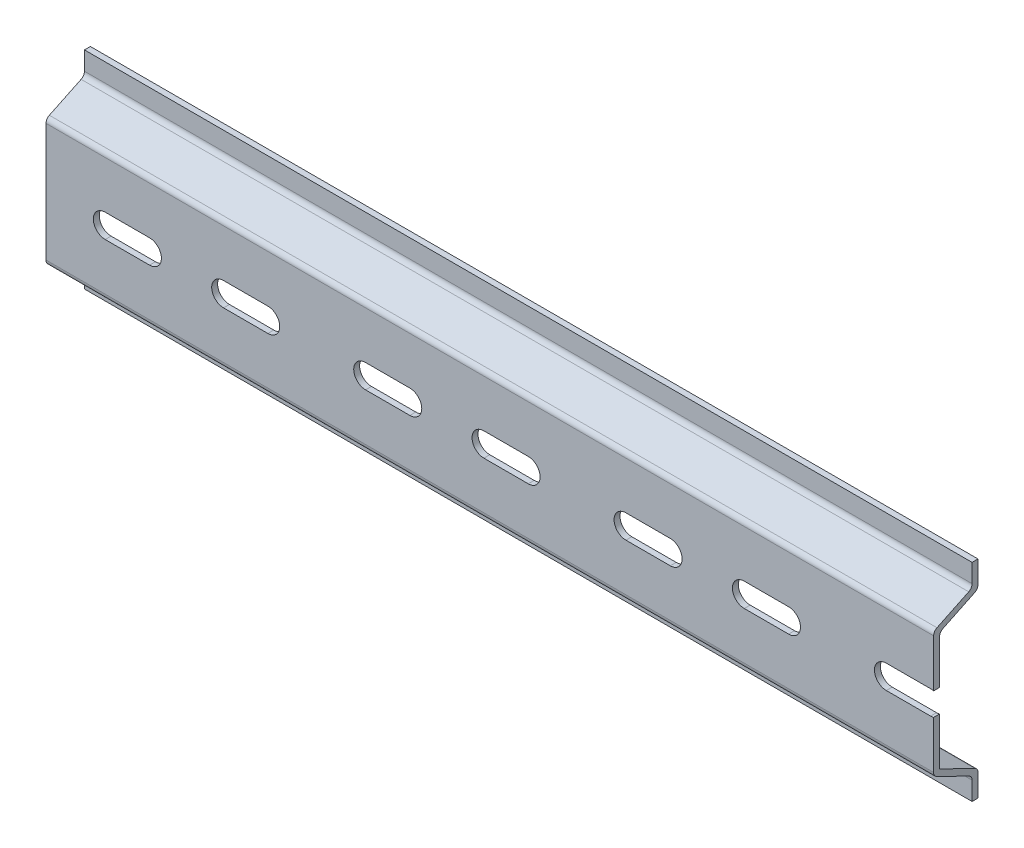
SolidWorks part; units mm, degrees
ref_plane "前视基准面" through (0, 0, 0) normal (0, 0, 1) x (1, 0, 0)
ref_plane "上视基准面" through (0, 0, 0) normal (0, 1, 0) x (1, 0, 0)
ref_plane "右视基准面" through (0, 0, 0) normal (1, 0, 0) x (0, 0, -1)
sketch "草图1" plane through (0, 0, 0) normal (1, 0, 0) x (0, 0, -1)
  line L0 (0, -10) -> (0, 10)
  line L1 (0, 10) -> (6.5, 13.1208)
  line L2 (6.5, 13.1208) -> (6.5, 17.5)
  line L3 (6.5, 17.5) -> (5.5, 17.5)
  line L4 (5.5, 17.5) -> (5.5, 13.75)
  line L5 (5.5, 13.75) -> (-1, 10.6292)
  line L6 (-1, 10.6292) -> (-1, -10.6292)
  line L7 (-14.3812, 0) -> (24.228, 0) construction
  line L8 (5.5, -13.75) -> (-1, -10.6292)
  line L9 (5.5, -17.5) -> (5.5, -13.75)
  line L10 (6.5, -17.5) -> (5.5, -17.5)
  line L11 (6.5, -13.1208) -> (6.5, -17.5)
  line L12 (0, -10) -> (6.5, -13.1208)
  point P12 (-1, 0)
  point P17 (0, 0)
  dimension "D1" = 7.5
  dimension "D2" = 1
  dimension "D3" = 1
  dimension "D4" = 1
  dimension "D5" = 27.5
  dimension "D6" = 35
  dimension "D7" = 20
extrude "凸台-拉伸1" add sketch "草图1" along normal blind 150
fillet "圆角1" radius 1 7 edges at (75, 13.75, -5.5) (75, 10.6292, 1) (75, 10, 0) (75, -10.6292, 1) (75, -13.1208, -6.5) (75, -13.75, -5.5) (75, 13.1208, -6.5)
sketch "草图2" plane through (0, 0, 0) normal (0, 0, -1) x (-1, 0, 0)
  line L0 (33.4315, 0) -> (-53.4315, 0) construction
  line L1 (-10, 0) -> (-17.5, 0) construction
  line L2 (-10, -2) -> (-17.5, -2)
  line L3 (-10, 2) -> (-17.5, 2)
  line L4 (-30, 0) -> (-37.5, 0) construction
  line L5 (-30, -2) -> (-37.5, -2)
  line L6 (-30, 2) -> (-37.5, 2)
  line L7 (-54, 0) -> (-61.5, 0) construction
  line L8 (-54, -2) -> (-61.5, -2)
  line L9 (-54, 2) -> (-61.5, 2)
  line L10 (-74, 0) -> (-81.5, 0) construction
  line L11 (-74, -2) -> (-81.5, -2)
  line L12 (-74, 2) -> (-81.5, 2)
  line L13 (-98, 0) -> (-105.5, 0) construction
  line L14 (-98, -2) -> (-105.5, -2)
  line L15 (-98, 2) -> (-105.5, 2)
  line L16 (-118, 0) -> (-125.5, 0) construction
  line L17 (-118, -2) -> (-125.5, -2)
  line L18 (-118, 2) -> (-125.5, 2)
  line L19 (-142, 0) -> (-149.5, 0) construction
  line L20 (-142, -2) -> (-149.5, -2)
  line L21 (-142, 2) -> (-149.5, 2)
  line L22 (-162, 0) -> (-169.5, 0) construction
  line L23 (-162, -2) -> (-169.5, -2)
  line L24 (-162, 2) -> (-169.5, 2)
  line L25 (-186, 0) -> (-193.5, 0) construction
  line L26 (-186, -2) -> (-193.5, -2)
  line L27 (-186, 2) -> (-193.5, 2)
  line L28 (-206, 0) -> (-213.5, 0) construction
  line L29 (-206, -2) -> (-213.5, -2)
  line L30 (-206, 2) -> (-213.5, 2)
  line L31 (-230, 0) -> (-237.5, 0) construction
  line L32 (-230, -2) -> (-237.5, -2)
  line L33 (-230, 2) -> (-237.5, 2)
  line L34 (-250, 0) -> (-257.5, 0) construction
  line L35 (-250, -2) -> (-257.5, -2)
  line L36 (-250, 2) -> (-257.5, 2)
  line L37 (-274, 0) -> (-281.5, 0) construction
  line L38 (-274, -2) -> (-281.5, -2)
  line L39 (-274, 2) -> (-281.5, 2)
  line L40 (-294, 0) -> (-301.5, 0) construction
  line L41 (-294, -2) -> (-301.5, -2)
  line L42 (-294, 2) -> (-301.5, 2)
  line L43 (-318, 0) -> (-325.5, 0) construction
  line L44 (-318, -2) -> (-325.5, -2)
  line L45 (-318, 2) -> (-325.5, 2)
  line L46 (-338, 0) -> (-345.5, 0) construction
  line L47 (-338, -2) -> (-345.5, -2)
  line L48 (-338, 2) -> (-345.5, 2)
  line L49 (-362, 0) -> (-369.5, 0) construction
  line L50 (-362, -2) -> (-369.5, -2)
  line L51 (-362, 2) -> (-369.5, 2)
  line L52 (-382, 0) -> (-389.5, 0) construction
  line L53 (-382, -2) -> (-389.5, -2)
  line L54 (-382, 2) -> (-389.5, 2)
  arc A0 (-10, -2) -> (-10, 2) centre (-10, 0) ccw
  arc A1 (-17.5, 2) -> (-17.5, -2) centre (-17.5, 0) ccw
  arc A2 (-30, -2) -> (-30, 2) centre (-30, 0) ccw
  arc A3 (-37.5, 2) -> (-37.5, -2) centre (-37.5, 0) ccw
  arc A4 (-54, -2) -> (-54, 2) centre (-54, 0) ccw
  arc A5 (-61.5, 2) -> (-61.5, -2) centre (-61.5, 0) ccw
  arc A6 (-74, -2) -> (-74, 2) centre (-74, 0) ccw
  arc A7 (-81.5, 2) -> (-81.5, -2) centre (-81.5, 0) ccw
  arc A8 (-98, -2) -> (-98, 2) centre (-98, 0) ccw
  arc A9 (-105.5, 2) -> (-105.5, -2) centre (-105.5, 0) ccw
  arc A10 (-118, -2) -> (-118, 2) centre (-118, 0) ccw
  arc A11 (-125.5, 2) -> (-125.5, -2) centre (-125.5, 0) ccw
  arc A12 (-142, -2) -> (-142, 2) centre (-142, 0) ccw
  arc A13 (-149.5, 2) -> (-149.5, -2) centre (-149.5, 0) ccw
  arc A14 (-162, -2) -> (-162, 2) centre (-162, 0) ccw
  arc A15 (-169.5, 2) -> (-169.5, -2) centre (-169.5, 0) ccw
  arc A16 (-186, -2) -> (-186, 2) centre (-186, 0) ccw
  arc A17 (-193.5, 2) -> (-193.5, -2) centre (-193.5, 0) ccw
  arc A18 (-206, -2) -> (-206, 2) centre (-206, 0) ccw
  arc A19 (-213.5, 2) -> (-213.5, -2) centre (-213.5, 0) ccw
  arc A20 (-230, -2) -> (-230, 2) centre (-230, 0) ccw
  arc A21 (-237.5, 2) -> (-237.5, -2) centre (-237.5, 0) ccw
  arc A22 (-250, -2) -> (-250, 2) centre (-250, 0) ccw
  arc A23 (-257.5, 2) -> (-257.5, -2) centre (-257.5, 0) ccw
  arc A24 (-274, -2) -> (-274, 2) centre (-274, 0) ccw
  arc A25 (-281.5, 2) -> (-281.5, -2) centre (-281.5, 0) ccw
  arc A26 (-294, -2) -> (-294, 2) centre (-294, 0) ccw
  arc A27 (-301.5, 2) -> (-301.5, -2) centre (-301.5, 0) ccw
  arc A28 (-318, -2) -> (-318, 2) centre (-318, 0) ccw
  arc A29 (-325.5, 2) -> (-325.5, -2) centre (-325.5, 0) ccw
  arc A30 (-338, -2) -> (-338, 2) centre (-338, 0) ccw
  arc A31 (-345.5, 2) -> (-345.5, -2) centre (-345.5, 0) ccw
  arc A32 (-362, -2) -> (-362, 2) centre (-362, 0) ccw
  arc A33 (-369.5, 2) -> (-369.5, -2) centre (-369.5, 0) ccw
  arc A34 (-382, -2) -> (-382, 2) centre (-382, 0) ccw
  arc A35 (-389.5, 2) -> (-389.5, -2) centre (-389.5, 0) ccw
  point P5 (-13.75, 0)
  point P14 (-33.75, 0)
  point P21 (-57.75, 0)
  point P28 (-77.75, 0)
  point P35 (-101.75, 0)
  point P42 (-121.75, 0)
  point P49 (-145.75, 0)
  point P56 (-165.75, 0)
  point P63 (-189.75, 0)
  point P70 (-209.75, 0)
  point P77 (-233.75, 0)
  point P84 (-253.75, 0)
  point P91 (-277.75, 0)
  point P98 (-297.75, 0)
  point P105 (-321.75, 0)
  point P112 (-341.75, 0)
  point P119 (-365.75, 0)
  point P126 (-385.75, 0)
  dimension "D1" = 2
  dimension "D2" = 7.5
  dimension "D3" = 10
  dimension "D4" = 2
  dimension "D5" = 9
extrude "切除-拉伸1" cut sketch "草图2" against normal blind 10
